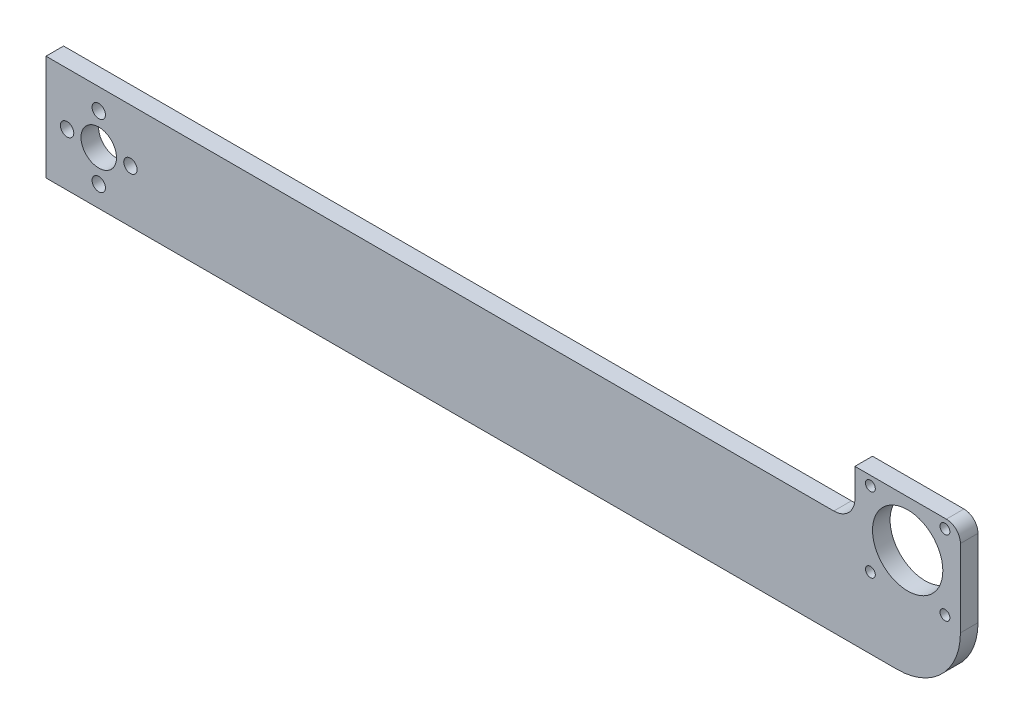
SolidWorks part; units mm, degrees
ref_plane "Front" through (0, 0, 0) normal (0, 0, 1) x (1, 0, 0)
ref_plane "Top" through (0, 0, 0) normal (0, 1, 0) x (1, 0, 0)
ref_plane "Right" through (0, 0, 0) normal (1, 0, 0) x (0, 0, -1)
sketch "Sketch1" plane through (0, 0, 0) normal (0, 0, 1) x (1, 0, 0)
  line L0 (278.638, 33.5448) -> (305.562, 33.5448) construction
  line L1 (-19.05, 19.05) -> (265.43, 19.05)
  line L2 (-19.05, 19.05) -> (-19.05, -19.05)
  line L3 (-19.05, -19.05) -> (286.1893, -19.05)
  line L5 (286.1893, -19.05) -> (288.29, -19.05)
  line L7 (273.05, 36.83) -> (311.15, 36.83)
  line L8 (311.15, 3.81) -> (311.15, 36.83)
  line L9 (273.05, 36.83) -> (273.05, 26.67)
  circle A0 centre (0, 0) radius 6.4135
  circle A1 centre (0, 11.43) radius 2.413
  circle A2 centre (0, 0) radius 11.43 construction
  circle A3 centre (11.43, 0) radius 2.413
  circle A4 centre (0, -11.43) radius 2.413
  circle A5 centre (-11.43, 0) radius 2.413
  arc A7 (288.29, -19.05) -> (311.15, 3.81) centre (288.29, 3.81) ccw
  circle A8 centre (292.1, 20.066) radius 12.7
  circle A9 centre (278.638, 33.5448) radius 1.778
  circle A10 centre (305.562, 33.5448) radius 1.778
  circle A11 centre (305.562, 6.5872) radius 1.778
  circle A12 centre (278.638, 6.5872) radius 1.778
  circle A13 centre (292.1, 20.066) radius 19.05 construction
  arc A15 (265.43, 19.05) -> (273.05, 26.67) centre (265.43, 26.67) ccw
  point P15 (0, 0)
  point P17 (-19.05, 0)
  point P23 (322.7312, -8.2659)
  point P37 (273.05, 19.05)
  point P38 (292.1, 36.83)
  dimension "D1" = 12.827
  dimension "D2" = 4.826
  dimension "D3" = 22.86
  dimension "D5" = 19.05
  dimension "D8" = 7.62
  dimension "D9" = 22.86
  dimension "D12" = 3.556
  dimension "D13" = 16.764
  dimension "D14" = 38.1
  dimension "D15" = 26.924
  dimension "D16" = 25.4
  dimension "D17" = 330.2
  dimension "D6" = 38.1
  dimension "D7" = 38.1
  dimension "D10" = 38.1
  dimension "D11" = 33.02
  dimension "D4" = 4
extrude "Boss-Extrude1" add sketch "Sketch1" along normal blind 6.35
fillet "Fillet1" radius 5.08 1 edges at (311.15, 36.83, 3.175)
